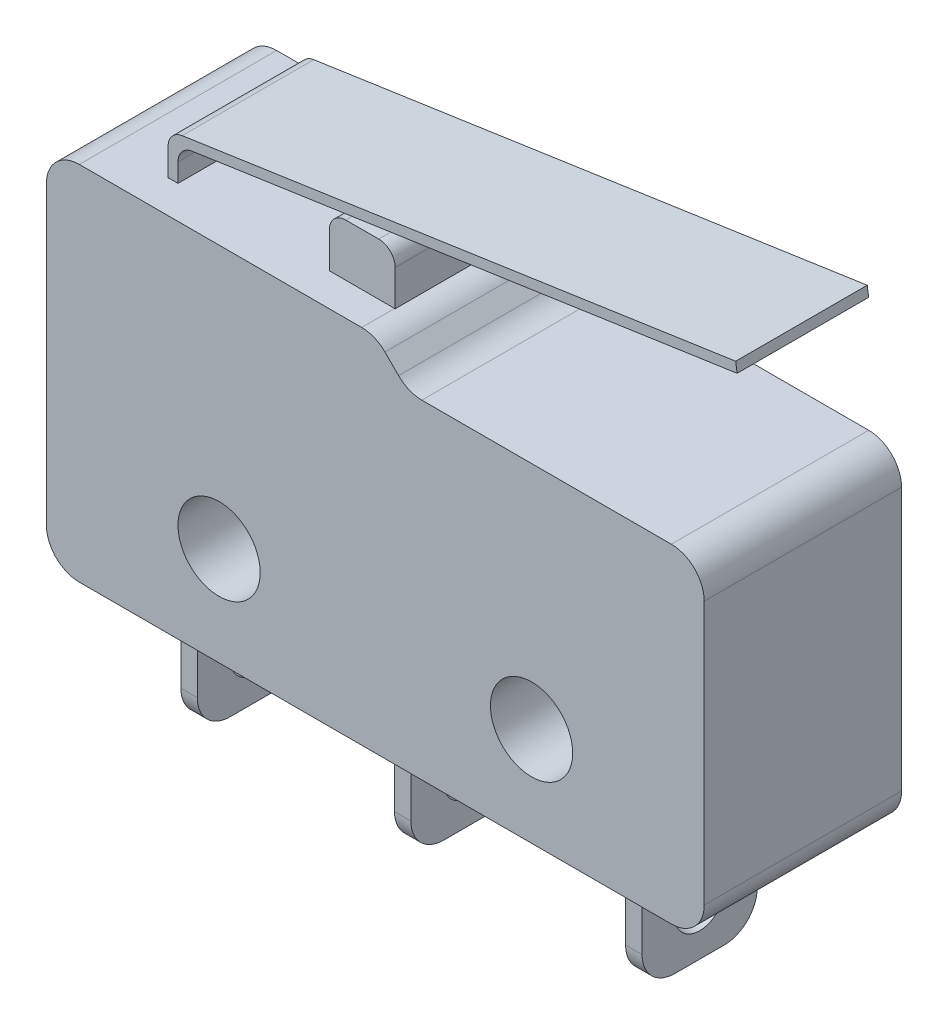
SolidWorks part; units mm, degrees
ref_plane "Front Plane" through (0, 0, 0) normal (0, 0, 1) x (1, 0, 0)
ref_plane "Top Plane" through (0, 0, 0) normal (0, 1, 0) x (1, 0, 0)
ref_plane "Right Plane" through (0, 0, 0) normal (1, 0, 0) x (0, 0, -1)
ref_plane "Plane1" through (0, 0, 1) normal (0, 0, -1) x (-1, 0, 0)
sketch "Sketch1" plane through (0, 0, 1) normal (0, 0, -1) x (-1, 0, 0)
  line L0 (4.7433, 8.0828) -> (4.0361, 7.3757)
  line L1 (4.0361, 7.3757) -> (12.3361, 7.3757)
  line L2 (12.3361, 7.3757) -> (12.3361, 9.6348)
  line L3 (12.3361, 9.6348) -> (12.0798, 9.6725)
  line L4 (12.0798, 9.6725) -> (12.0361, 9.3757)
  line L5 (12.0361, 9.3757) -> (12.0361, 8.3757)
  line L6 (12.0361, 8.3757) -> (5.4504, 8.3757)
  arc A0 (5.4504, 8.3757) -> (4.7433, 8.0828) centre (5.4504, 7.3757) ccw
extrude "Boss-Extrude1" add sketch "Sketch1" against normal blind 4
sketch "Sketch2" plane through (0, 0, 5) normal (0, 0, 1) x (1, 0, 0)
  line L0 (-12.3361, 7.3757) -> (-12.3361, 9.6348)
  line L1 (-12.3361, 9.6348) -> (-12.0798, 9.6725)
  line L2 (-12.0798, 9.6725) -> (-12.0361, 9.3757)
  line L3 (-12.0361, 9.3757) -> (-12.0361, 8.3757)
  line L4 (-12.0361, 8.3757) -> (-5.4504, 8.3757)
  line L5 (-4.7433, 8.0828) -> (-4.0361, 7.3757)
  line L6 (-4.0361, 7.3757) -> (-12.3361, 7.3757)
  arc A0 (-5.4504, 8.3757) -> (-4.7433, 8.0828) centre (-5.4504, 7.3757) cw
extrude "Boss-Extrude2" add sketch "Sketch2" along normal blind 1
sketch "Sketch3" plane through (0, 0, 6) normal (0, 0, 1) x (1, 0, 0)
  line L0 (-12.0361, 8.3757) -> (-12.0361, 9.3757)
  line L1 (-12.0361, 9.3757) -> (-12.0798, 9.6725)
  line L2 (-12.0798, 9.6725) -> (-12.3361, 9.6348)
  line L3 (-12.3361, 9.6348) -> (-12.3361, 8.3757)
  line L4 (-12.3361, 8.3757) -> (-12.0361, 8.3757)
extrude "Cut-Extrude1" cut sketch "Sketch3" against normal blind 1
sketch "Sketch4" plane through (0, 7.3757, 0) normal (0, -1, 0) x (1, 0, 0)
  line L0 (-4.0361, 1) -> (-12.3361, 1)
  line L1 (-12.3361, 1) -> (-12.3361, 6)
  line L2 (-12.3361, 6) -> (-4.0361, 6)
  line L3 (-4.0361, 6) -> (-4.0361, 1)
extrude "Boss-Extrude3" add sketch "Sketch4" along normal blind 10
sketch "Sketch5" plane through (-4.0361, 0, 0) normal (1, 0, 0) x (0, 0, -1)
  line L0 (-1, 7.3757) -> (-1, -2.6243)
  line L1 (-1, -2.6243) -> (-6, -2.6243)
  line L2 (-6, -2.6243) -> (-6, 7.3757)
  line L3 (-6, 7.3757) -> (-1, 7.3757)
extrude "Boss-Extrude4" add sketch "Sketch5" along normal blind 9
sketch "Sketch6" plane through (-10.4318, -1.5341, 0) normal (0.9894, 0.1455, 0) x (0, 0, -1)
  line L0 (-1, 11.3271) -> (-1, 11.0271)
  line L1 (-1, 11.0271) -> (-5, 11.0271)
  line L2 (-5, 11.0271) -> (-5, 11.3271)
  line L3 (-5, 11.3271) -> (-1, 11.3271)
extrude "Boss-Extrude5" add sketch "Sketch6" along normal blind 17.1828
sketch "Sketch7" plane through (-12.3361, 0, 0) normal (-1, 0, 0) x (0, 0, 1)
  line L0 (1, -2.6243) -> (1, 8.3757)
  line L1 (1, 8.3757) -> (6, 8.3757)
  line L2 (6, 8.3757) -> (6, -2.6243)
  line L3 (6, -2.6243) -> (1, -2.6243)
extrude "Boss-Extrude6" add sketch "Sketch7" along normal blind 2.7
sketch "Sketch8" plane through (0, 0, 1) normal (0, 0, -1) x (-1, 0, 0)
  line L0 (15.0361, 8.3757) -> (15.0361, -2.6243)
  line L1 (15.0361, -2.6243) -> (-4.9639, -2.6243)
  line L2 (-4.9639, -2.6243) -> (-4.9639, 7.3757)
  line L3 (-4.9639, 7.3757) -> (4.0361, 7.3757)
  line L4 (4.0361, 7.3757) -> (4.7433, 8.0828)
  line L5 (5.4504, 8.3757) -> (15.0361, 8.3757)
  arc A0 (4.7433, 8.0828) -> (5.4504, 8.3757) centre (5.4504, 7.3757) cw
extrude "Boss-Extrude7" add sketch "Sketch8" along normal blind 1
sketch "Sketch9" plane through (0, 8.3757, 0) normal (0, 1, 0) x (-1, 0, 0)
  line L0 (7.4326, 1) -> (5.4326, 1)
  line L1 (5.4326, 1) -> (5.4326, 5)
  line L2 (5.4326, 5) -> (7.4326, 5)
  line L3 (7.4326, 5) -> (7.4326, 1)
extrude "Boss-Extrude8" add sketch "Sketch9" along normal blind 1.5866
sketch "Sketch10" plane through (0, -2.6243, 0) normal (0, -1, 0) x (1, 0, 0)
  line L0 (-5.7035, 4.75) -> (-5.2035, 4.75)
  line L1 (-5.2035, 4.75) -> (-5.2035, 1.25)
  line L2 (-5.2035, 1.25) -> (-5.7035, 1.25)
  line L3 (-5.7035, 1.25) -> (-5.7035, 4.75)
extrude "Boss-Extrude9" add sketch "Sketch10" along normal blind 3.5
sketch "Sketch11" plane through (0, -2.6243, 0) normal (0, -1, 0) x (1, 0, 0)
  line L0 (1.3227, 4.75) -> (1.8227, 4.75)
  line L1 (1.8227, 4.75) -> (1.8227, 1.25)
  line L2 (1.8227, 1.25) -> (1.3227, 1.25)
  line L3 (1.3227, 1.25) -> (1.3227, 4.75)
extrude "Boss-Extrude10" add sketch "Sketch11" along normal blind 3.5
sketch "Sketch12" plane through (0, -2.6243, 0) normal (0, -1, 0) x (1, 0, 0)
  line L0 (-12.1987, 4.75) -> (-11.6987, 4.75)
  line L1 (-11.6987, 4.75) -> (-11.6987, 1.25)
  line L2 (-11.6987, 1.25) -> (-12.1987, 1.25)
  line L3 (-12.1987, 1.25) -> (-12.1987, 4.75)
extrude "Boss-Extrude11" add sketch "Sketch12" along normal blind 3.5
hole_wizard "Ø2.5 (2.5) Diameter Hole1" positions "Sketch14" profile "Sketch13" hole size "Ø2.5" standard "ANSI Metric"
sketch "Sketch14" plane through (0, 0, 6) normal (0, 0, 1) x (1, 0, 0)
  point P0 (-9.7861, 0.3757)
  point P1 (-0.2861, 0.3757)
sketch "Sketch13" plane through (-9.7861, 0.3757, 6) normal (1, 0, 0) x (0, -1, 0)
  line L0 (0, 0) -> (0, 6)
  line L1 (0, 6) -> (1.25, 6)
  line L2 (1.25, 6) -> (1.25, 0)
  line L5 (1.25, 0) -> (0, 0)
  line L11 (0, -6.35) -> (0, 107.95) construction
  dimension "Thru Hole Dia." = 2.5
  dimension "Thru Hole Depth" = 6
hole_wizard "Ø1.5 (1.5) Diameter Hole1" positions "Sketch16" profile "Sketch15" hole size "Ø1.5" standard "ANSI Metric"
sketch "Sketch16" plane through (-11.6987, 0, 0) normal (1, 0, 0) x (0, 0, -1)
  point P0 (-3, -4.6243)
sketch "Sketch15" plane through (-11.6987, -4.6243, 3) normal (0, 1, 0) x (0, 0, -1)
  line L0 (0, 0) -> (0, 3.3375)
  line L1 (0, 3.3375) -> (0.75, 3.3375)
  line L2 (0.75, 3.3375) -> (0.75, 0)
  line L5 (0.75, 0) -> (0, 0)
  line L11 (0, -6.35) -> (0, 107.95) construction
  dimension "Thru Hole Dia." = 1.5
  dimension "Thru Hole Depth" = 3.3375
hole_wizard "Ø1.5 (1.5) Diameter Hole2" positions "Sketch18" profile "Sketch17" hole size "Ø1.5" standard "ANSI Metric"
sketch "Sketch18" plane through (1.8227, 0, 0) normal (1, 0, 0) x (0, 0, -1)
  point P0 (-3, -4.6243)
sketch "Sketch17" plane through (1.8227, -4.6243, 3) normal (0, 1, 0) x (0, 0, -1)
  line L0 (0, 0) -> (0, 0.5)
  line L1 (0, 0.5) -> (0.75, 0.5)
  line L2 (0.75, 0.5) -> (0.75, 0)
  line L5 (0.75, 0) -> (0, 0)
  line L11 (0, -6.35) -> (0, 107.95) construction
  dimension "Thru Hole Dia." = 1.5
  dimension "Thru Hole Depth" = 0.5
hole_wizard "Ø1.5 (1.5) Diameter Hole3" positions "Sketch20" profile "Sketch19" hole size "Ø1.5" standard "ANSI Metric"
sketch "Sketch20" plane through (-5.2035, 0, 0) normal (1, 0, 0) x (0, 0, -1)
  point P0 (-3, -4.6243)
sketch "Sketch19" plane through (-5.2035, -4.6243, 3) normal (0, 1, 0) x (0, 0, -1)
  line L0 (0, 0) -> (0, 9.8326)
  line L1 (0, 9.8326) -> (0.75, 9.8326)
  line L2 (0.75, 9.8326) -> (0.75, 0)
  line L5 (0.75, 0) -> (0, 0)
  line L11 (0, -6.35) -> (0, 107.95) construction
  dimension "Thru Hole Dia." = 1.5
  dimension "Thru Hole Depth" = 9.8326
fillet "Fillet1" radius 0.5 4 edges at (-5.4326, 9.9623, 3) (-12.3361, 9.6348, 3) (-7.4326, 9.9623, 3) (-12.0361, 9.3757, 3)
fillet "Fillet2" radius 1 11 edges at (4.9639, -2.6243, 3) (-15.0361, 8.3757, 3) (-4.0361, 7.3757, 3) (-11.9487, -6.1243, 1.25) (-5.4535, -6.1243, 1.25) (4.9639, 7.3757, 3) (-5.4535, -6.1243, 4.75) (-15.0361, -2.6243, 3) (1.5727, -6.1243, 1.25) (1.5727, -6.1243, 4.75) (-11.9487, -6.1243, 4.75)
